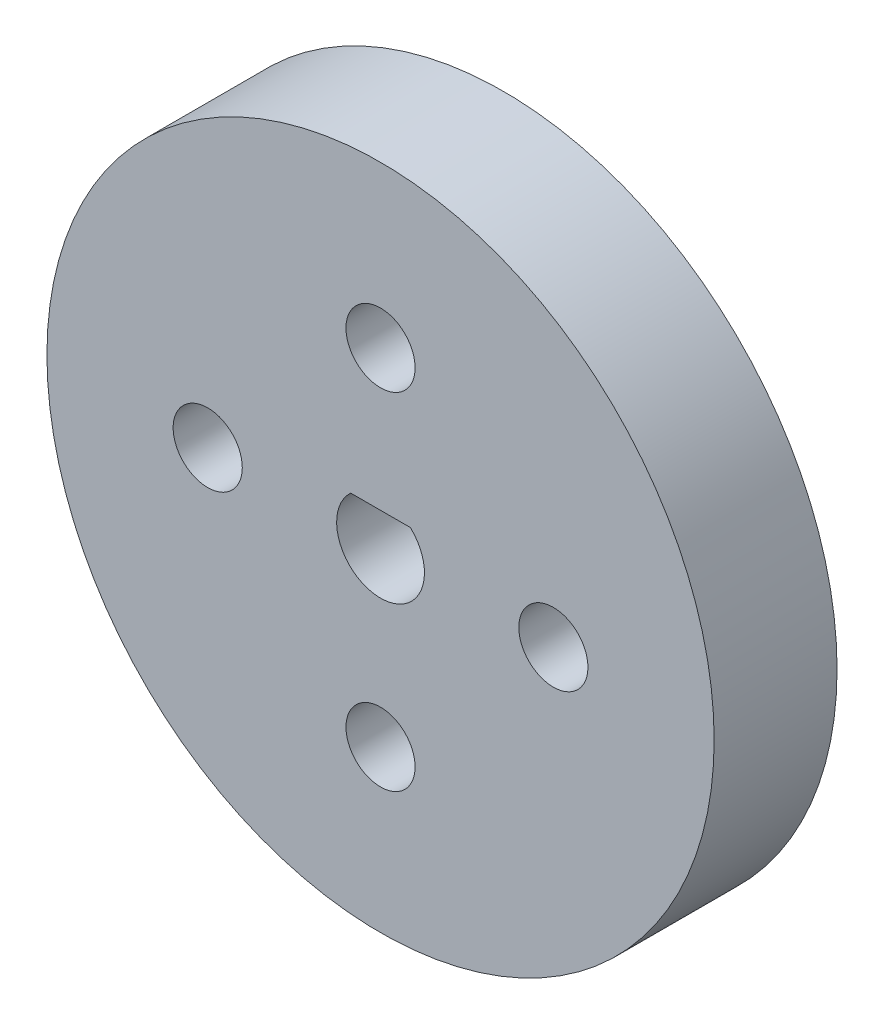
SolidWorks part; units mm, degrees
ref_plane "Front Plane" through (0, 0, 0) normal (0, 0, 1) x (1, 0, 0)
ref_plane "Top Plane" through (0, 0, 0) normal (0, 1, 0) x (1, 0, 0)
ref_plane "Right Plane" through (0, 0, 0) normal (1, 0, 0) x (0, 0, -1)
sketch "Sketch1" plane through (0, 0, 0) normal (0, 0, 1) x (1, 0, 0)
  circle A0 centre (0, 0) radius 14.478
extrude "Boss-Extrude1" add sketch "Sketch1" along normal blind 5.334
sketch "Sketch2" plane through (0, 0, 5.334) normal (0, 0, 1) x (1, 0, 0)
  circle A0 centre (0, 0) radius 1.905
extrude "Cut-Extrude2" cut sketch "Sketch2" against normal up to surface (5.334 mm away) up to face at (14.478, 0, 0)
sketch "Sketch3" plane through (0, 0, 5.334) normal (0, 0, 1) x (1, 0, 0)
  line L0 (-1.2952, 1.397) -> (1.2952, 1.397)
  line L1 (0, 1.397) -> (0, -1.905) construction
  circle A0 centre (0, 0) radius 1.905 construction
  arc A1 (-1.2952, 1.397) -> (1.2952, 1.397) centre (0, 0) cw
  dimension "D1" = 3.302
extrude "Boss-Extrude3" add sketch "Sketch3" against normal blind 5.334
sketch "Sketch4" plane through (0, 0, 0) normal (0, 0, -1) x (-1, 0, 0)
  line L0 (0, 0) -> (0, -7.5) construction
  line L1 (0, 0) -> (12.024, 0) construction
  line L2 (0, 0) -> (6.9018, -6.9018) construction
  line L3 (0, 0) -> (6.9018, 6.9018) construction
  circle A0 centre (0, -7.5) radius 1.5
  circle A1 centre (7.5, 0) radius 1.5
  circle A2 centre (-7.5, 0) radius 1.5
  circle A3 centre (0, 7.5) radius 1.5
  dimension "D2" = 3
  dimension "D1" = 7.5
extrude "Cut-Extrude4" cut sketch "Sketch4" against normal through all
equation "\"material_thickness\"= 0.21"
equation "\"D1@Boss-Extrude1\"=\"material_thickness\""
